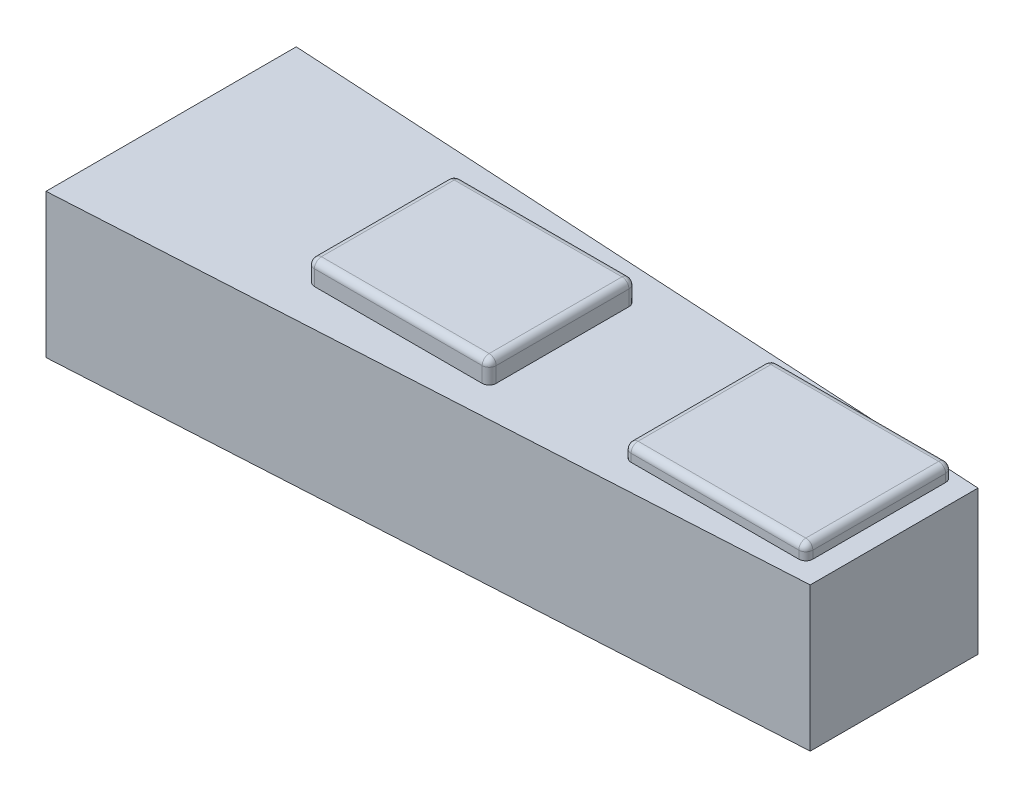
SolidWorks part; units mm, degrees
material "1060 Alloy"
ref_plane "Front Plane" through (0, 0, 0) normal (0, 0, 1) x (1, 0, 0)
ref_plane "Top Plane" through (0, 0, 0) normal (0, 1, 0) x (1, 0, 0)
ref_plane "Right Plane" through (0, 0, 0) normal (1, 0, 0) x (0, 0, -1)
sketch "Sketch1" plane through (0, 0, 0) normal (0, 1, 0) x (1, 0, 0)
  line L0 (0, -89.5) -> (0, 89.5)
  line L1 (517.1593, -60) -> (517.1593, 60)
  line L2 (0, 89.5) -> (517.1593, 60)
  line L3 (0, -89.5) -> (517.1593, -60)
  point P4 (0, 0)
  point P8 (517.1593, 0)
  dimension "D1" = 179
  dimension "D2" = 120
  dimension "D3" = 518
  dimension "D4" = 518
extrude "Boss-Extrude1" add sketch "Sketch1" along normal blind 103
fillet "Fillet1" radius 0.0001 12 edges at (0, 0, 0) (0, 51.5, -89.5) (258.5797, 0, -74.75) (517.1593, 51.5, -60) (517.1593, 0, 0) (517.1593, 51.5, 60) (258.5797, 0, 74.75) (0, 51.5, 89.5) (0, 103, 0) (517.1593, 103, 0) (258.5797, 103, -74.75) (258.5797, 103, 74.75)
sketch "Sketch2" plane through (0, 103, 0) normal (0, 1, 0) x (1, 0, 0)
  line L0 (517.1592, -59.9999) -> (517.1592, 59.9999) construction
  line L1 (372.1592, -48.151) -> (502.1592, -48.151)
  line L2 (372.1592, -48.151) -> (372.1592, 56.849)
  line L3 (372.1592, 56.849) -> (502.1592, 56.849)
  line L4 (502.1592, -48.151) -> (502.1592, 56.849)
  line L5 (372.1592, -48.151) -> (502.1592, 56.849) construction
  line L6 (372.1592, 56.849) -> (502.1592, -48.151) construction
  line L7 (517.1592, 59.9999) -> (0.0001, 89.4999) construction
  point P0 (437.1592, 4.349)
  dimension "D1" = 130
  dimension "D2" = 105
  dimension "D3" = 15
  dimension "D4" = 4
extrude "Boss-Extrude2" add sketch "Sketch2" along normal blind 10.6
fillet "Fillet2" radius 5 8 edges at (502.1592, 108.3, -56.849) (372.1592, 108.3, -56.849) (372.1592, 108.3, 48.151) (372.1592, 113.6, -4.349) (437.1592, 113.6, -56.849) (502.1592, 113.6, -4.349) (502.1592, 108.3, 48.151) (437.1592, 113.6, 48.151)
sketch "Sketch3" plane through (0, 103, 0) normal (0, 1, 0) x (1, 0, 0)
  line L0 (0.0001, 89.4999) -> (0.0001, -89.4999) construction
  line L1 (150.0001, -52.5) -> (280.0001, -52.5)
  line L2 (150.0001, -52.5) -> (150.0001, 52.5)
  line L3 (150.0001, 52.5) -> (280.0001, 52.5)
  line L4 (280.0001, -52.5) -> (280.0001, 52.5)
  line L5 (150.0001, -52.5) -> (280.0001, 52.5) construction
  line L6 (150.0001, 52.5) -> (280.0001, -52.5) construction
  line L9 (0, 0) -> (346.7055, 0) construction
  point P0 (215.0001, 0)
  dimension "D1" = 130
  dimension "D2" = 105
  dimension "D3" = 150
extrude "Boss-Extrude3" add sketch "Sketch3" along normal blind 16
fillet "Fillet3" radius 5 8 edges at (215.0001, 119, 52.5) (150.0001, 119, 0) (215.0001, 119, -52.5) (280.0001, 119, 0) (280.0001, 111, -52.5) (150.0001, 111, 52.5) (150.0001, 111, -52.5) (280.0001, 111, 52.5)
sketch "Sketch4" plane through (0, 0, 0) normal (0, -1, 0) x (1, 0, 0)
  line L2 (517.1593, 59.9999) -> (517.1593, -59.9999) construction
  circle A0 centre (479.1593, 0) radius 15
  dimension "D1" = 30
  dimension "D2" = 38
extrude "Cut-Extrude1" cut sketch "Sketch4" against normal blind 104 and the other way through all
sketch "Sketch5" plane through (0, 0, 0) normal (0, -1, 0) x (1, 0, 0)
  line L0 (0, 0) -> (334.9405, 0) construction
  circle A0 centre (255, 0) radius 15
  dimension "D1" = 30
  dimension "D2" = 255
extrude "Cut-Extrude2" cut sketch "Sketch5" against normal blind 104
